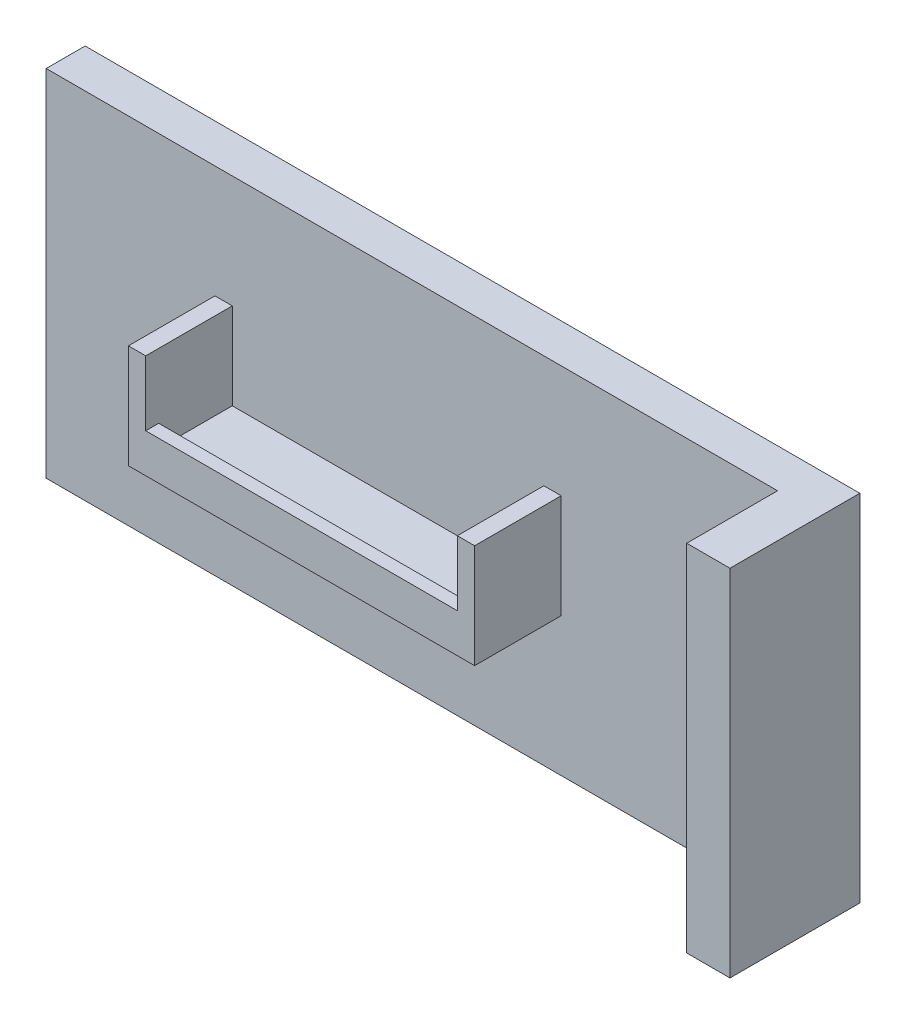
SolidWorks part; units mm, degrees
ref_plane "Plan de face" through (0, 0, 0) normal (0, 0, 1) x (1, 0, 0)
ref_plane "Plan de dessus" through (0, 0, 0) normal (0, 1, 0) x (1, 0, 0)
ref_plane "Plan de droite" through (0, 0, 0) normal (1, 0, 0) x (0, 0, -1)
sketch "Esquisse1" plane through (0, 0, 0) normal (0, 0, 1) x (1, 0, 0)
  line L1 (0, 0) -> (-169, 0)
  line L2 (0, 0) -> (0, 82)
  line L3 (0, 82) -> (-169, 82)
  line L4 (-169, 0) -> (-169, 82)
  dimension "D1" = 169
  dimension "D2" = 82
extrude "Boss.-Extru.1" add sketch "Esquisse1" along normal blind 9
sketch "Esquisse2" plane through (0, 82, 0) normal (0, 1, 0) x (1, 0, 0)
  line L1 (0, 0) -> (0, -20)
  line L2 (0, 0) -> (-169, 0) construction
  line L3 (0, 0) -> (10, 0)
  line L4 (0, 0) -> (0, -30)
  line L5 (0, -30) -> (10, -30)
  line L6 (10, 0) -> (10, -30)
  dimension "D1" = 10
  dimension "D2" = 30
extrude "Boss.-Extru.2" add sketch "Esquisse2" against normal blind 82 contours L4 L3 L6 L5
sketch "Esquisse3" plane through (0, 0, 9) normal (0, 0, 1) x (1, 0, 0)
  line L0 (-169, 32) -> (-0.8706, 32) construction
  line L5 (-130, 36) -> (-50, 36)
  line L6 (-130, 36) -> (-130, 32)
  line L7 (-130, 32) -> (-50, 32)
  line L8 (-50, 36) -> (-50, 32)
  line L17 (-169, 82) -> (-169, 0) construction
  line L18 (0, 82) -> (-169, 82) construction
  dimension "D1" = 4
  dimension "D2" = 80
  dimension "D3" = 39
  dimension "D4" = 46
extrude "Boss.-Extru.4" add sketch "Esquisse3" along normal blind 20
sketch "Esquisse4" plane through (0, 36, 0) normal (0, 1, 0) x (1, 0, 0)
  line L0 (-50, -29) -> (-130, -29) construction
  line L1 (-50, -9) -> (-54, -9)
  line L2 (-50, -9) -> (-50, -29)
  line L3 (-50, -29) -> (-54, -29)
  line L4 (-54, -9) -> (-54, -29)
  dimension "D1" = 4
extrude "Boss.-Extru.5" add sketch "Esquisse4" along normal blind 20
sketch "Esquisse5" plane through (0, 36, 0) normal (0, 1, 0) x (1, 0, 0)
  line L0 (-54, -29) -> (-130, -29) construction
  line L1 (-130, -9) -> (-126, -9)
  line L2 (-130, -9) -> (-130, -29)
  line L3 (-130, -29) -> (-126, -29)
  line L4 (-126, -9) -> (-126, -29)
  dimension "D1" = 4
extrude "Boss.-Extru.6" add sketch "Esquisse5" along normal blind 20
sketch "Esquisse6" plane through (0, 36, 0) normal (0, 1, 0) x (1, 0, 0)
  line L0 (-54, -9) -> (-54, -29) construction
  line L1 (-126, -29) -> (-54, -29)
  line L2 (-126, -29) -> (-126, -26)
  line L3 (-126, -26) -> (-54, -26)
  line L4 (-54, -29) -> (-54, -26)
  dimension "D1" = 3
extrude "Boss.-Extru.7" add sketch "Esquisse6" along normal blind 5
